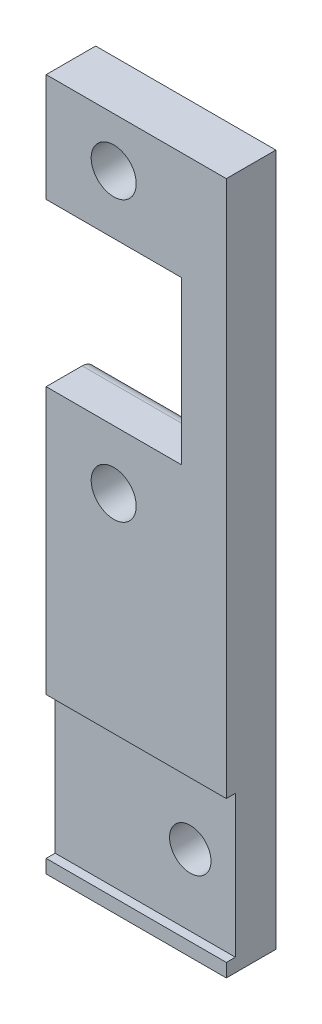
SolidWorks part; units mm, degrees
ref_plane "Front Plane" through (0, 0, 0) normal (0, 0, 1) x (1, 0, 0)
ref_plane "Top Plane" through (0, 0, 0) normal (0, 1, 0) x (1, 0, 0)
ref_plane "Right Plane" through (0, 0, 0) normal (1, 0, 0) x (0, 0, -1)
sketch "ProfileSketch3" plane through (0, 0, 0) normal (0, 0, 1) x (1, 0, 0)
  line L0 (0, 46.85) -> (15, 46.85)
  line L1 (0, 0) -> (20, 0)
  line L2 (0, 0) -> (0, 46.85)
  line L4 (20, 0) -> (20, 76.85)
  line L5 (15, 46.85) -> (15, 64.85)
  line L6 (15, 64.85) -> (0, 64.85)
  line L7 (0, 64.85) -> (0, 76.85)
  line L8 (0, 76.85) -> (20, 76.85)
  circle A0 centre (7.5, 40.35) radius 2.5
  circle A1 centre (7.5, 71.35) radius 2.5
  circle A3 centre (15, 9.375) radius 2.3
  dimension "D8" = 5
  dimension "D12" = 4.6
  dimension "D6" = 20
  dimension "D1" = 46.85
  dimension "D4" = 12
  dimension "D5" = 5.5
  dimension "D7" = 6.5
  dimension "D3" = 31
  dimension "D10" = 18
  dimension "D11" = 6.5
  dimension "D2" = 7.5
  dimension "D9" = 5
  dimension "D13" = 5
  dimension "D15" = 9.375
extrude "ProfileBoss-Extrude1" add sketch "ProfileSketch3" along normal blind 5.5
fillet "Fillet1" radius 1.5 2 edges at (7.5, 46.85, 0) (7.5, 64.85, 0)
sketch "Sketch1" plane through (0, 0, 5.5) normal (0, 0, 1) x (1, 0, 0)
  line L0 (0, 46.85) -> (0, 0) construction
  line L1 (0, 1.5) -> (20, 1.5)
  line L2 (0, 1.5) -> (0, 17.25)
  line L3 (0, 17.25) -> (20, 17.25)
  line L4 (20, 1.5) -> (20, 17.25)
  line L5 (20, 0) -> (20, 76.85) construction
  line L6 (0, 0) -> (20, 0) construction
  dimension "D1" = 1.5
  dimension "D2" = 15.75
  dimension "D3" = 7.875
  dimension "D4" = 7.875
extrude "SlidingMountCut-Extrude1" cut sketch "Sketch1" against normal blind 1
equation "\"SK8RodShaftSupportHeight\"= 42mm"
equation "\"SK8RodShaftSupportLength\"= 15mm"
equation "\"SK8MountHoleDiameter\"= 5mm"
equation "\"SK8RiserWidth\"= 6.75mm'Measured to meet Nema17 Mount Hole Center axis"
equation "\"SK8MountHoleFromSide\"= \"SK8RodShaftSupportLength\" / 2"
equation "\"SK8MountHoleFromEitherEnd\"= 5.5mm"
equation "\"MicroSwitchCutOutLength\"= 13.05mm"
equation "\"MicroSwitchHeight\"= 6.55mm"
equation "\"MicroSwitchMountingHoleOffsetFromSide\"= 3.35mm"
equation "\"MicroSwitchTerminalHeight\"= 3.5mm"
equation "\"MicroSwitchExtraMountingHeight\"= 2mm"
equation "\"MicroSwitchDepth\"= 2.8mm"
equation "\"MicroSwitchMountingHoleOffsetFromBottom\"= 7mm"
equation "\"M2HeatInsertHoleDiameter\"= 3mm + .1mm'Add .1mm for printing"
equation "\"M2HeatInsertHoleDepth\"= 3.1mm'Spec"
equation "\"D1@ProfileBoss-Extrude1\"=\"YAxisHolderThickness\""
equation "\"MicroSwitchCutOutHeight\"= \"MicroSwitchExtraMountingHeight\" + \"MicroSwitchTerminalHeight\" + \"MicroSwitchHeight\""
equation "\"EndStopCableWidth\"= 3.75mm"
equation "\"EndStopCableDepth\"= 1.75mm"
equation "\"D6@ProfileSketch3\"= \"YEndStopHolderLength\""
equation "\"D1@ProfileSketch3\"=\"MicroSwitchCutOutLength\" + \"SK8MountHoleFromEitherEnd\" * 1.6 +25mm"
equation "\"D4@ProfileSketch3\"=12mm"
equation "\"D5@ProfileSketch3\"=\"SK8MountHoleFromEitherEnd\""
equation "\"D8@ProfileSketch3\"=\"SK8MountHoleDiameter\""
equation "\"Nema17StepperMountSlotDistance\"=31"
equation "\"D3@ProfileSketch3\"=\"Nema17StepperMountSlotDistance\""
equation "\"D2@ProfileSketch3\"=\"SK8RodShaftSupportLength\"/2"
equation "\"M3HeatInsertDiameter\"=4.6"
equation "\"YAxisHolderThickness\"= \"M3HeatInsertHoleDepth\""
equation "\"YEndStopHolderLength\"= \"SK8RodShaftSupportLength\" + \"YEndStopBaseExtraLength\""
equation "\"YEndStopBaseExtraLength\"= 5mm"
equation "\"D9@ProfileSketch3\"=\"YEndStopBaseExtraLength\""
equation "\"M3HeatInsertHoleDepth\"= 5.5mm"
equation "\"D13@ProfileSketch3\"=\"YEndStopBaseExtraLength\""
equation "\"YAxisEndStopMicroSwitchHolderHeight\"= 18.75'Same as XAxisMircoSwitchHolder"
equation "\"YAxisEndStopMicroSwitchHolderWidth\"= 29.05mm'Same as XAxisMicroSwitchHolder"
equation "\"D12@ProfileSketch3\"=\"M3HeatInsertDiameter\""
equation "\"D15@ProfileSketch3\"=\"YAxisEndStopMicroSwitchHolderHeight\"/2"
equation "\"D2@Sketch1\"=\"YAxisEndStopMicroSwitchHolderHeight\" -\"EndStopSlidingMountWallWidth\" *2"
equation "\"EndStopSlidingMountWallWidth\"= 1.5mm"
equation "\"D1@Sketch1\"=\"EndStopSlidingMountWallWidth\""
equation "\"EndStopSlidingMountDepth\"= 1mm"
equation "\"D1@SlidingMountCut-Extrude1\" = \"EndStopSlidingMountDepth\""
equation "\"EndStopSlidingMountWallPrintOffset\"= .05mm"
